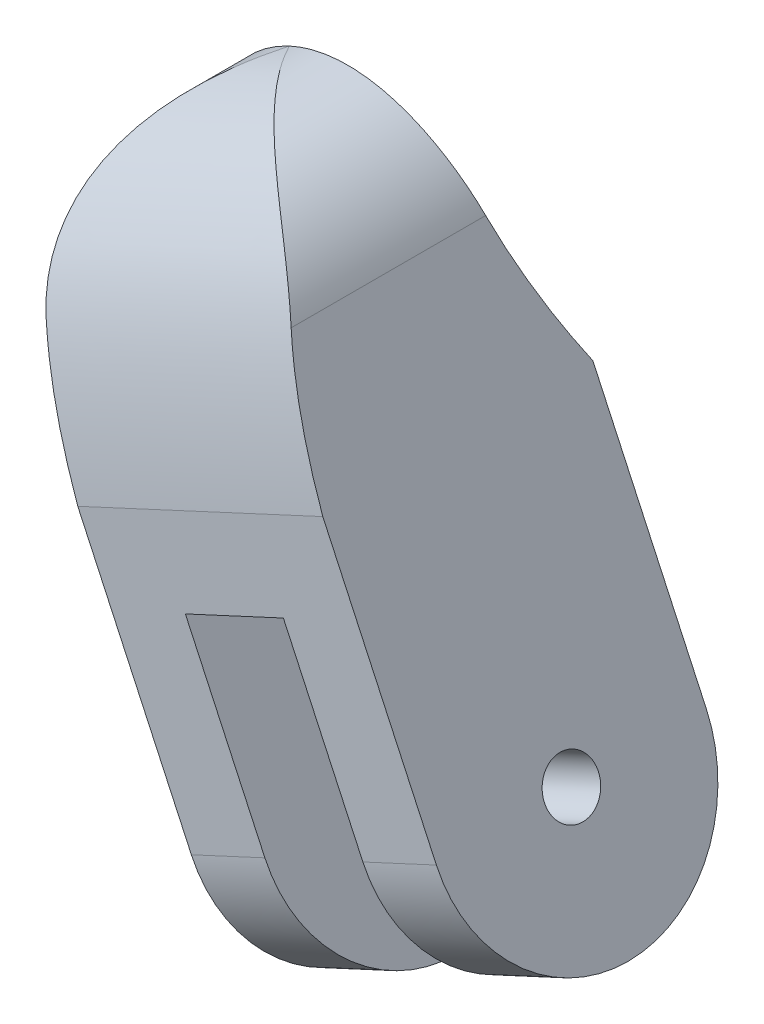
SolidWorks part; units mm, degrees
ref_plane "Plan de face" through (0, 0, 0) normal (0, 0, 1) x (1, 0, 0)
ref_plane "Plan de dessus" through (0, 0, 0) normal (0, 1, 0) x (1, 0, 0)
ref_plane "Plan de droite" through (0, 0, 0) normal (1, 0, 0) x (0, 0, -1)
sketch "Esquisse1" plane through (0, 0, 0) normal (0, 0, 1) x (1, 0, 0)
  line L0 (-117.6444, 150.8915) -> (-107.1302, 128.2099)
  line L1 (-117.6444, 150.8915) -> (-108.5718, 155.0972)
  line L2 (-107.1302, 128.2099) -> (-98.0576, 132.4156)
  line L3 (-108.5718, 155.0972) -> (-98.0576, 132.4156)
  line L4 (-117.6444, 150.8915) -> (-98.0576, 132.4156) construction
  line L5 (-107.1302, 128.2099) -> (-108.5718, 155.0972) construction
  line L6 (-103.6453, 132.5809) -> (-112.0567, 150.7262) construction
  line L7 (-104.4084, 129.4716) -> (-109.4552, 140.3588)
  line L8 (-109.4552, 140.3588) -> (-105.8262, 142.041)
  line L9 (-105.8262, 142.041) -> (-100.7794, 131.1539)
  point P1 (-107.851, 141.6535)
  point P3 (0, 0)
  point P11 (0, 0)
  point P14 (-107.851, 141.6535)
  dimension "D1" = 10
  dimension "D2" = 25
  dimension "D3" = 3
  dimension "D4" = 4
  dimension "D5" = 12
extrude "Boss.-Extru.1" add sketch "Esquisse1" along normal blind 10 contours L8 L9 L2 L3 L1 L0 L7
sketch "Esquisse2" plane through (-39.2611, -18.1997, 0) normal (-0.9073, -0.4206, 0) x (0, 0, 1)
  line L0 (0, 176.3754) -> (10, 176.3754) construction
  line L1 (0, 186.3754) -> (10, 186.3754)
  line L2 (0, 186.3754) -> (0, 166.3754)
  line L4 (10, 186.3754) -> (10, 166.3754)
  line L5 (10, 176.3754) -> (9.3061, 186.3754) construction
  line L6 (9.3061, 186.3754) -> (2.5, 186.3754) construction
  line L7 (0, 186.3754) -> (5, 176.3754) construction
  line L8 (5, 176.3754) -> (5, 186.3754) construction
  line L9 (5, 186.3754) -> (0, 176.3754) construction
  line L10 (2.5, 181.3754) -> (2.5, 186.3754) construction
  line L12 (2.5, 186.3754) -> (2.4887, 181.392) construction
  line L13 (2.4887, 181.392) -> (0, 176.3754) construction
  line L14 (10, 186.3754) -> (0, 186.3754) construction
  line L15 (2.5, 186.3754) -> (5, 186.3754)
  line L16 (0, 176.3754) -> (0, 166.3754)
  line L17 (0, 166.3754) -> (0, 161.3754)
  line L18 (10, 176.3754) -> (10, 166.3754)
  line L19 (10, 161.3754) -> (0, 161.3754) construction
  line L20 (0, 186.3754) -> (0, 161.3754) construction
  line L21 (0, 161.3754) -> (10, 161.3754)
  line L22 (10, 161.3754) -> (10, 166.3754)
  line L23 (0, 166.3754) -> (10, 166.3754) construction
  arc A0 (10, 166.3754) -> (0, 166.3754) centre (5, 166.3754) cw
  circle A1 centre (5, 166.3754) radius 1
  spline S0 degree 2 poles (10, 176.3754) (9.3061, 186.3754) (2.5, 186.3754) knots 0 0 0 1 1 1
  spline S1 degree 2 poles (2.5, 186.3754) (2.4887, 181.392) (0, 176.3754) knots 0 0 0 1 1 1
  point P5 (0, 0)
  point P11 (0, 0)
  point P13 (5, 176.3754)
  point P17 (0, 0)
  point P28 (5, 166.3754)
  dimension "D1" = 14
  dimension "D2" = 10.4
  dimension "D3" = 10
  dimension "D6" = 2
  dimension "D4" = 5.6
  dimension "D5" = 5
extrude "Enlèv. mat.-Extru.1" cut sketch "Esquisse2" against normal blind 10
sketch "Esquisse4" plane through (0, 0, 0) normal (0, 0, -1) x (-1, 0, 0)
  line L0 (108.5718, 155.0972) -> (98.0576, 132.4156)
  line L1 (98.0576, 132.4156) -> (107.1302, 128.2099)
  line L2 (107.1302, 128.2099) -> (117.6444, 150.8915)
  line L3 (117.6444, 150.8915) -> (108.5718, 155.0972)
  line L4 (106.4689, 150.5608) -> (115.5416, 146.3552) construction
  arc A0 (106.4689, 150.5608) -> (115.5416, 146.3552) centre (111.0053, 148.458) cw
  dimension "D1" = 5
extrude "Enlèv. mat.-Extru.3" cut sketch "Esquisse4" against normal blind 20 contours L0 A0 L3 | L3 A0 L2
